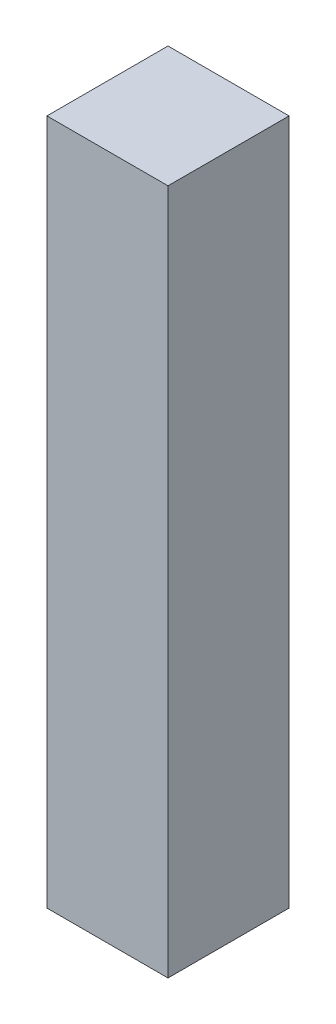
SolidWorks part; units mm, degrees
material "AISI 1020"
ref_plane "Front Plane" through (0, 0, 0) normal (0, 0, 1) x (1, 0, 0)
ref_plane "Top Plane" through (0, 0, 0) normal (0, 1, 0) x (1, 0, 0)
ref_plane "Right Plane" through (0, 0, 0) normal (1, 0, 0) x (0, 0, -1)
sketch "Sketch1" plane through (0, 0, 0) normal (0, 1, 0) x (1, 0, 0)
  line L1 (-480.2083, 235.4167) -> (-180.2083, 235.4167)
  line L2 (-480.2083, 235.4167) -> (-480.2083, -64.5833)
  line L3 (-480.2083, -64.5833) -> (-180.2083, -64.5833)
  line L4 (-180.2083, 235.4167) -> (-180.2083, -64.5833)
  dimension "D1" = 300
extrude "Boss-Extrude1" add sketch "Sketch1" along normal blind 1700
